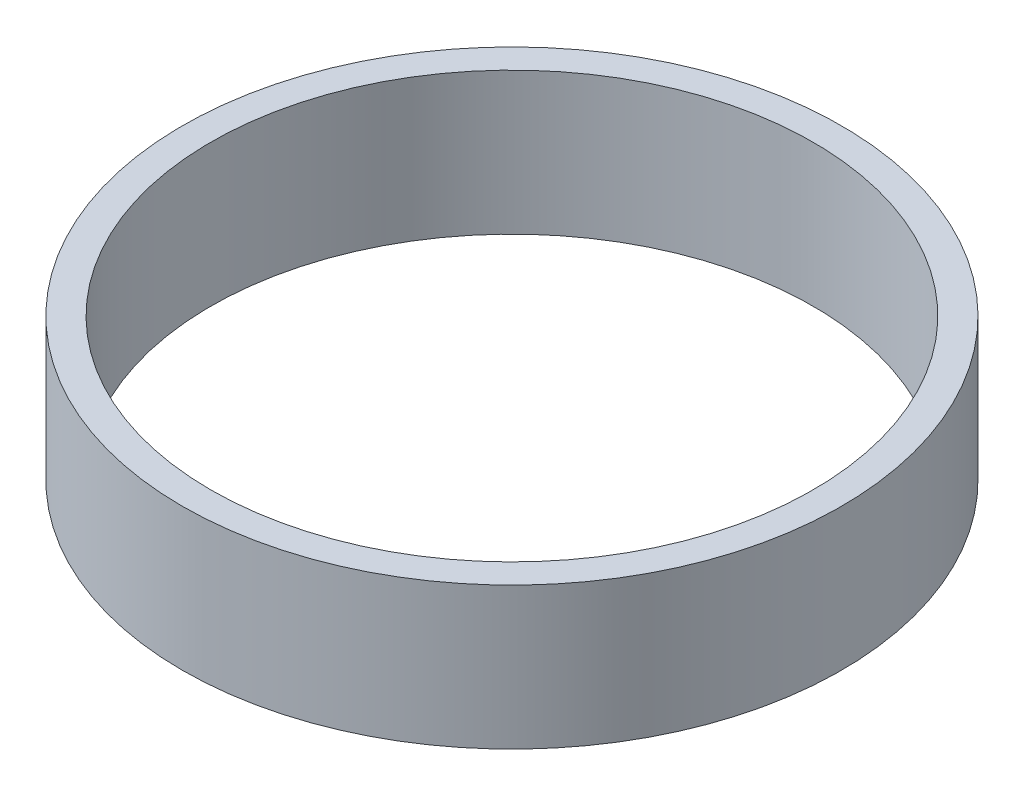
SolidWorks part; units mm, degrees
ref_plane "Спереди" through (0, 0, 0) normal (0, 0, 1) x (1, 0, 0)
ref_plane "Сверху" through (0, 0, 0) normal (0, 1, 0) x (1, 0, 0)
ref_plane "Справа" through (0, 0, 0) normal (1, 0, 0) x (0, 0, -1)
sketch "Эскиз1" plane through (0, 0, 0) normal (0, 1, 0) x (1, 0, 0)
  circle A0 centre (0, 0) radius 11.6
  circle A1 centre (0, 0) radius 10.6
  dimension "D1" = 21.2
  dimension "D2" = 23.2
extrude "тело" add sketch "Эскиз1" along normal blind 5
